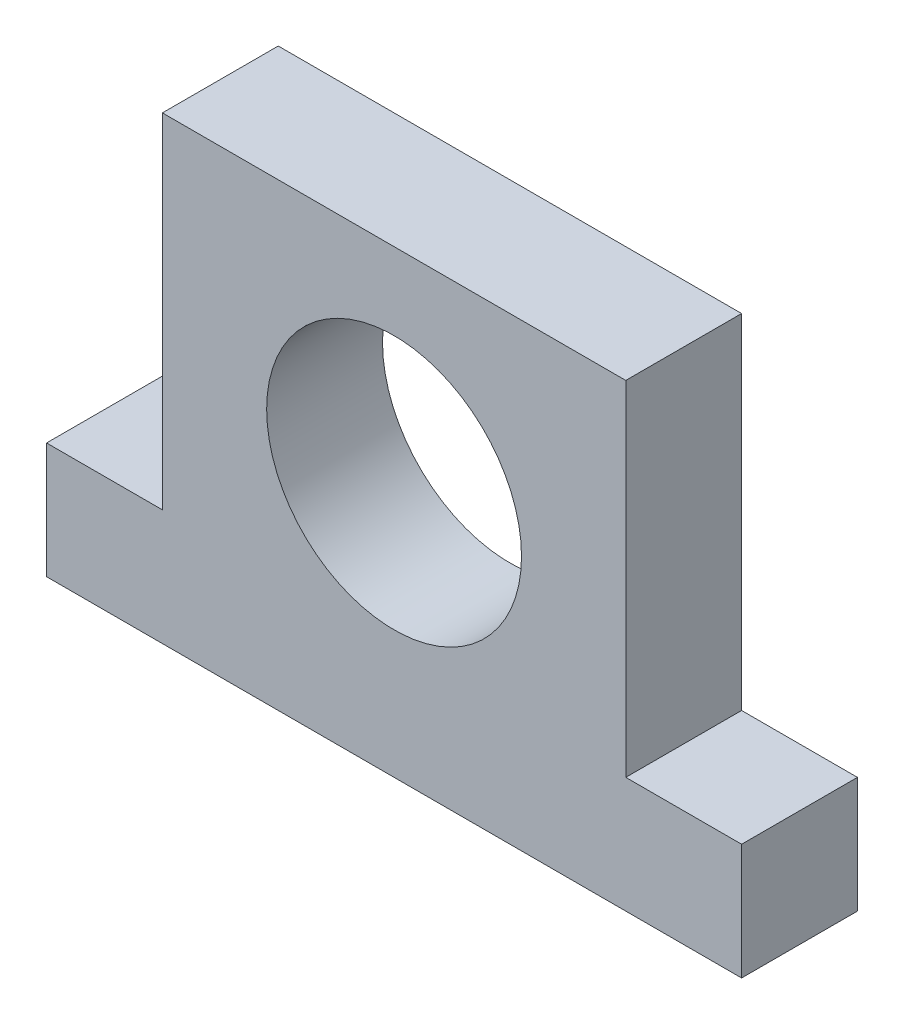
SolidWorks part; units mm, degrees
ref_plane "Front Plane" through (0, 0, 0) normal (0, 0, 1) x (1, 0, 0)
ref_plane "Top Plane" through (0, 0, 0) normal (0, 1, 0) x (1, 0, 0)
ref_plane "Right Plane" through (0, 0, 0) normal (1, 0, 0) x (0, 0, -1)
sketch "Sketch1" plane through (0, 0, 0) normal (0, 0, 1) x (1, 0, 0)
  line L0 (0, 0) -> (10, 0)
  line L1 (10, 0) -> (10, 29.6765)
  line L2 (10, 29.6765) -> (50, 29.6765)
  line L3 (50, 29.6765) -> (50, 0)
  line L4 (50, 0) -> (60, 0)
  line L5 (60, 0) -> (60, -10)
  line L6 (60, -10) -> (0, -10)
  line L7 (0, -10) -> (0, 0)
  circle A0 centre (30, 12.0263) radius 11
  point P11 (0, 0)
  point P12 (0, 0)
  point P13 (30, 29.6765)
  dimension "D1" = 22
  dimension "D2" = 20
  dimension "D3" = 10
  dimension "D4" = 10
  dimension "D5" = 10
extrude "Boss-Extrude1" add sketch "Sketch1" along normal blind 10
